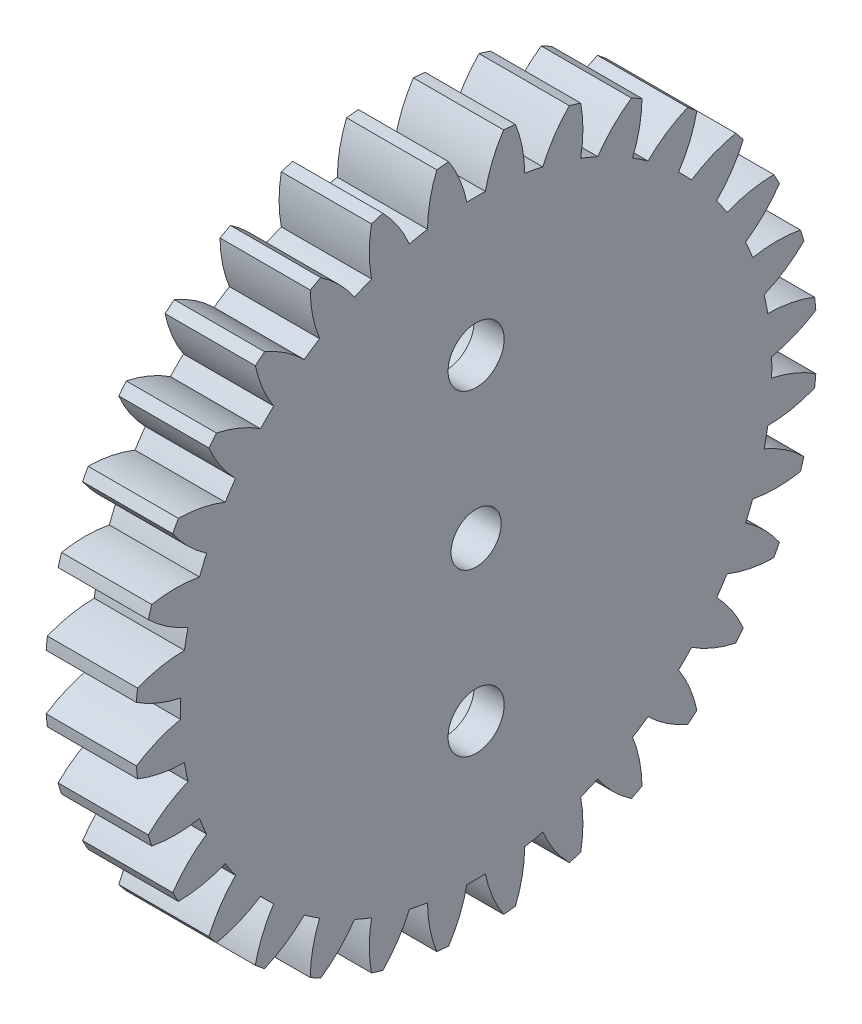
SolidWorks part; units mm, degrees
ref_plane "Plane1" through (0, 0, 0) normal (0, 0, 1) x (1, 0, 0)
ref_plane "Plane2" through (0, 0, 0) normal (0, 1, 0) x (1, 0, 0)
ref_plane "Plane3" through (0, 0, 0) normal (1, 0, 0) x (0, 0, -1)
sketch "HoldingSke" plane through (0, 0, 0) normal (0, 1, 0) x (1, 0, 0)
  line L0 (0, 0) -> (0.848, -0.5299)
  line L1 (-15, 0) -> (100, 0) construction
  line L2 (0, 0) -> (-2.1039, 2.3779)
  line L3 (0, 0) -> (-11.863, 4.5341)
  line L4 (0, 0) -> (7.3237, 4.5764)
  line L5 (0, 0) -> (-46.8476, -17.4728)
  line L6 (0, 0) -> (-3.0672, -2.0694)
  line L7 (-2.1039, 2.3779) -> (8.6588, 51.2068)
  line L8 (-76.2, 54.61) -> (-75.9, 54.61)
  line L9 (-71.009, 38.7566) -> (-53.1078, 45.2721)
  line L10 (-76.2, 71.12) -> (104.1128, 71.12)
  line L11 (0, 0) -> (-3.7, 0)
  line L12 (-76.2, 101.6) -> (-76.162, 101.6)
  line L13 (24.9733, 27.94) -> (52.9518, 28.4284)
  line L14 (24.9733, 27.94) -> (24.9743, 27.94)
  line L15 (24.9733, 27.94) -> (100.4006, 29.5858)
  line L16 (-63.627, -1) -> (-12.827, -1)
  circle A0 centre (0, 0) radius 1
  circle A1 centre (0, 0) radius 14.749
  circle A2 centre (0, 0) radius 37.5
  circle A3 centre (0, 0) radius 1.25
  dimension "MHD" = 29.498
  dimension "Hub_dia" = 75
  dimension "Bore" = 2
  dimension "MBD" = 2.5
  dimension "Num_teeth" = 32
  dimension "Pitch" = 1
  dimension "Overall_len" = 50
  dimension "Show_teeth" = 32
  dimension "Thickness" = 3.7
  dimension "OAL" = 50.001
  dimension "T_dim" = 0.3
  dimension "Ap" = 20
  dimension "H" = 19.05
  dimension "Pitch_radius" = 180.3128
  dimension "Width" = 3.7
  dimension "Backlash" = 0.038
  dimension "Addendum_fac" = 1
  dimension "Dedendum_fac" = 1.25
  dimension "Clearance_fac" = 0.25
  dimension "Dedendum_add" = 0.001
  dimension "Module" = 1
sketch "BasProSke" plane through (0, 0, 0) normal (0, 1, 0) x (1, 0, 0)
  line L0 (-10, 0) -> (60, 0) construction
  line L1 (0, 0) -> (0, 17)
  line L2 (0, 0) -> (4.5, 0)
  line L3 (4.5, 0) -> (4.5, 17)
  line L4 (4.5, 17) -> (0, 17)
  dimension "Thickness" = 4.5
  dimension "Diameter" = 34
revolve "Base-Revolve" add sketch "BasProSke" angle 360 about L0
sketch "TooCutSke" plane through (0, 0, 0) normal (1, 0, 0) x (0, 0, -1)
  line L1 (0, 0) -> (0, 107) construction
  line L2 (0, 0) -> (-0.8516, 15.9773) construction
  line L3 (0, 0) -> (-3.1334, 31.8138) construction
  line L4 (-0.8516, 15.9773) -> (-1.5667, 15.9069) construction
  arc A0 (0.462, 14.7418) -> (-0.462, 14.7418) centre (0, 0) ccw
  arc A1 (1.3867, 16.9688) -> (-1.3867, 16.9688) centre (0, 0) ccw
  circle A2 centre (0, 0) radius 16 construction
  circle A3 centre (0, 0) radius 15.0351 construction
  arc A4 (-0.462, 14.7418) -> (-1.3867, 16.9688) centre (-6.7293, 13.4451) ccw
  arc A5 (1.3867, 16.9688) -> (0.462, 14.7418) centre (6.7293, 13.4451) ccw
  dimension "Root_dia" = 29.498
  dimension "Overcut_dia" = 34.0508
  dimension "Pitch_dia" = 32
  dimension "Base_dia" = 30.0702
  dimension "Flank_rad" = 6.4
  dimension "Half_ang" = 5.625
  dimension "Half_CT" = 0.7186
extrude "ToothCut" cut sketch "TooCutSke" along normal through all
fillet "Breaks" [suppressed] radius 0.02
fillet "RootFillets" [suppressed] radius 0.251
pattern_circular "TeethCuts" count 32 every 11.25 about axis through (-10, 0, 0) along (1, 0, 0) of "ToothCut", "RootFillets", "Breaks"
sketch "HubNeaOneSke" plane through (0, 0, 0) normal (-1, 0, 0) x (0, 0, 1)
  circle A0 centre (0, 0) radius 14.749
  dimension "Diameter" = 29.498
extrude "HubNearOne" [suppressed] add sketch "HubNeaOneSke" along normal blind 45.501
sketch "HubNeaBotSke" plane through (0, 0, 0) normal (-1, 0, 0) x (0, 0, 1)
  circle A0 centre (0, 0) radius 14.749
  dimension "Diameter" = 29.498
extrude "HubNearBoth" [suppressed] add sketch "HubNeaBotSke" along normal blind 22.7505
ref_plane "FarPln" through (4.5, 0, 0) normal (1, 0, 0) x (0, 0, -1)
sketch "HubFarSke" plane through (4.5, 0, 0) normal (1, 0, 0) x (0, 0, -1)
  circle A0 centre (0, 0) radius 14.749
  dimension "Diameter" = 29.498
extrude "HubFar" [suppressed] add sketch "HubFarSke" along normal blind 22.7505
sketch "BorSke" plane through (0, 0, 0) normal (1, 0, 0) x (0, 0, -1)
  circle A0 centre (0, 0) radius 1.25
  dimension "Diameter" = 2.5
extrude "Bore" cut sketch "BorSke" along normal mid plane 100.0019
sketch "KeySke" plane through (0, 0, 0) normal (1, 0, 0) x (0, 0, -1)
  line L0 (-0.4, 0) -> (-0.4, 1.55)
  line L1 (-0.4, 1.55) -> (0.4, 1.55)
  line L2 (0.4, 1.55) -> (0.4, 0)
  line L3 (0, 0) -> (0, 34) construction
  line L4 (-0.4, 0) -> (0.4, 0)
  dimension "Offset" = 1.55
  dimension "Width" = 0.8
extrude "Keyway" [suppressed] cut sketch "KeySke" along normal mid plane 100.0019
pattern_circular "Keyway2" [suppressed] count 2 every 90 about axis through (-10, 0, 0) along (1, 0, 0)
extrude "Cut-Extrude5" cut sketch "Sketch5" against normal blind 3.7
sketch "Sketch5" plane through (4.5, -86.5551, 116.6893) normal (1, 0, 0) x (0, 0, -1)
  circle A0 centre (-107.057, 115.3942) radius 1.25
  point P3 (257.8573, 53.7538)
sketch "Sketch7" plane through (4.5, 0, 0) normal (1, 0, 0) x (0, 0, -1)
  circle A0 centre (0, 0) radius 2.75
  dimension "D1" = 5.5
sketch "Sketch8" plane through (4.5, 0, 0) normal (1, 0, 0) x (0, 0, -1)
  line L0 (0, 7.9) -> (0, -7.9) construction
  circle A0 centre (0, 7.9) radius 1.4
  circle A1 centre (0, -7.9) radius 1.4
  point P4 (0, 0)
  point P5 (0, 0)
  point P6 (0, 0)
  point P10 (0, 0)
  point P11 (0, 0)
  point P13 (0, 8.8146)
  point P15 (0, 6.0602)
  point P16 (0, 6.4861)
  point P17 (0, 0)
  point P18 (0, 6.2874)
  point P19 (0, 0)
  point P20 (0, -7.0237)
  point P21 (0, -7.5377)
  dimension "D1" = 2.8
  dimension "D2" = 15.8
extrude "Cut-Extrude8" cut sketch "Sketch8" against normal through all
sketch "Sketch9" plane through (0, 0, 0) normal (-1, 0, 0) x (0, 0, 1)
  circle A0 centre (0, 7.9) radius 2.5
  circle A1 centre (0, -7.9) radius 2.5
  dimension "D1" = 5
extrude "Cut-Extrude9" cut sketch "Sketch9" against normal blind 3
equation "' \"Module@HoldingSke\" = 6.35"
equation "' \"Num_teeth@HoldingSke\" = 12"
equation "' \"Ap@HoldingSke\" =  20"
equation "' \"Ap@HoldingSke\" = 20"
equation "' \"Width@HoldingSke\" = 0.5 * 25.4"
equation "' \"Hub_dia@HoldingSke\"= 1 * 25.4"
equation "' \"Hub_dia@HoldingSke\" = 1 * 25.4"
equation "' \"Overall_len@HoldingSke\" = 1.0 * 25.4"
equation "' \"Bore@HoldingSke\" = 0.75 * 25.4"
equation "' \"T_dim@HoldingSke\" = 0.1 * 25.4"
equation "' \"Width@KeySke\" = 0.25 * 25.4"
equation "' \"Show_teeth@HoldingSke\" = 13"
equation "' \"Backlash@HoldingSke\" = 0.009 * 25.4"
equation "' \"Addendum_fac@HoldingSke\" = 1.0"
equation "' \"Dedendum_fac@HoldingSke\" = 1.25"
equation "' \"Dedendum_add@HoldingSke\" = 0.00005 * 25.4"
equation "' \"Clearance_fac@HoldingSke\" = 0.25"
equation "\"Pitch@HoldingSke\" = 1 / \"Module@HoldingSke\""
equation "\"Overcut_dia@TooCutSke\" = (\"Num_teeth@HoldingSke\" + 2 * \"Addendum_fac@HoldingSke\") / \"Pitch@HoldingSke\" + 0.002 * 25.4"
equation "\"Pitch_dia@TooCutSke\" = \"Num_teeth@HoldingSke\" / \"Pitch@HoldingSke\""
equation "\"Base_dia@TooCutSke\" = \"Num_teeth@HoldingSke\" / \"Pitch@HoldingSke\" * cos((\"Ap@HoldingSke\"  * 3.14159265 / 180))"
equation "\"Root_dia@TooCutSke\" = (\"Num_teeth@HoldingSke\" + 2) / \"Pitch@HoldingSke\" - 2 * (\"Addendum_fac@HoldingSke\" + \"Dedendum_fac@HoldingSke\") / \"Pitch@HoldingSke\" - \"Dedendum_add@HoldingSke\" * 2"
equation "\"Half_ang@TooCutSke\" = 180 / \"Num_teeth@HoldingSke\""
equation "\"Half_CT@TooCutSke\" = \"Num_teeth@HoldingSke\" / \"Pitch@HoldingSke\" * sin((3.14159265 / 2 / \"Num_teeth@HoldingSke\")) / 2 - 7 * \"Backlash@HoldingSke\" / 4"
equation "\"Flank_rad@TooCutSke\" = \"Num_teeth@HoldingSke\" / \"Pitch@HoldingSke\" / 5"
equation "\"Radius@RootFillets\" = \"Clearance_fac@HoldingSke\" / \"Pitch@HoldingSke\" + \"Dedendum_add@HoldingSke\""
equation "\"Break_rad@Breaks\" = 0.02 / \"Pitch@HoldingSke\""
equation "\"Thickness@HoldingSke\" = \"Width@HoldingSke\""
equation "\"OAL@HoldingSke\" = \"Thickness@HoldingSke\""
equation "\"MHD@HoldingSke\" = (\"Num_teeth@HoldingSke\" + 2) / \"Pitch@HoldingSke\" - 2 * (\"Addendum_fac@HoldingSke\" + \"Dedendum_fac@HoldingSke\")  / \"Pitch@HoldingSke\" - \"Dedendum_add@HoldingSke\" * 2"
equation "\"MBD@HoldingSke\" = (\"Num_teeth@HoldingSke\" + 2) / \"Pitch@HoldingSke\" - 2 * (\"Addendum_fac@HoldingSke\" + \"Dedendum_fac@HoldingSke\")  / \"Pitch@HoldingSke\" - \"Dedendum_add@HoldingSke\" * 2 - 0.002 * 25.4"
equation "\"MHD@HoldingSke\" = ((sgn( \"MHD@HoldingSke\" - \"Hub_dia@HoldingSke\" )-1)*( \"MHD@HoldingSke\" - \"Hub_dia@HoldingSke\" ))/-2+ \"Hub_dia@HoldingSke\""
equation "\"MBD@HoldingSke\"= 2.5mm"
equation "\"OAL@HoldingSke\" = ((sgn( \"OAL@HoldingSke\" - \"Overall_len@HoldingSke\" )+1)*( \"OAL@HoldingSke\" - \"Overall_len@HoldingSke\" ))/2 + \"Overall_len@HoldingSke\" + 0.000002 * 25.4"
equation "\"Num_teeth@TeethCuts\" = int( \"Show_teeth@HoldingSke\" ) + 1"
equation "\"Num_teeth@TeethCuts\" = ((sgn( \"Num_teeth@TeethCuts\" - \"Num_teeth@HoldingSke\" )-1)*( \"Num_teeth@TeethCuts\" - \"Num_teeth@HoldingSke\" ))/-2+ \"Num_teeth@HoldingSke\""
equation "\"Num_teeth@TeethCuts\" = ((sgn( \"Num_teeth@TeethCuts\" - 2.0)+1)*( \"Num_teeth@TeethCuts\" - 2.0))/2 +2.0"
equation "\"Angle@TeethCuts\" = 360.0 / \"Num_teeth@HoldingSke\""
equation "\"Diameter@BasProSke\" = (\"Num_teeth@HoldingSke\" + 2 * \"Addendum_fac@HoldingSke\") / \"Pitch@HoldingSke\""
equation "\"Thickness@BasProSke\"=4.5mm"
equation "' \"Fillet_rad@BasProSke\" =  \"Thickness@HoldingSke\" * 0.05"
equation "' \"Fillet_rad@BasProSke\" = \"Thickness@HoldingSke\" * 0.05"
equation "\"MHD@HoldingSke\" = ((sgn( \"MHD@HoldingSke\" - \"Root_dia@TooCutSke\" )-1)*( \"MHD@HoldingSke\" - \"Root_dia@TooCutSke\" ))/-2+ \"Root_dia@TooCutSke\""
equation "\"Diameter@HubNeaOneSke\" = \"MHD@HoldingSke\""
equation "\"Length@HubNearOne\" = \"OAL@HoldingSke\" - \"Thickness@BasProSke\""
equation "\"Diameter@HubNeaBotSke\" = \"MHD@HoldingSke\""
equation "\"Length@HubNearBoth\" = ( \"OAL@HoldingSke\" - \"Thickness@BasProSke\" ) / 2.0"
equation "\"Thickness@FarPln\"= 4.5mm"
equation "\"Diameter@HubFarSke\" = \"MHD@HoldingSke\""
equation "\"Length@HubFar\" = ( \"OAL@HoldingSke\" - \"Thickness@BasProSke\" ) / 2.0"
equation "\"Diameter@BorSke\" = \"MBD@HoldingSke\""
equation "\"D1@Bore\" = \"OAL@HoldingSke\" * 2.0"
equation "\"D1@Keyway\" = \"OAL@HoldingSke\" * 2.0"
equation "\"Offset@KeySke\" = \"T_dim@HoldingSke\" + \"MBD@HoldingSke\" / 2.0"
